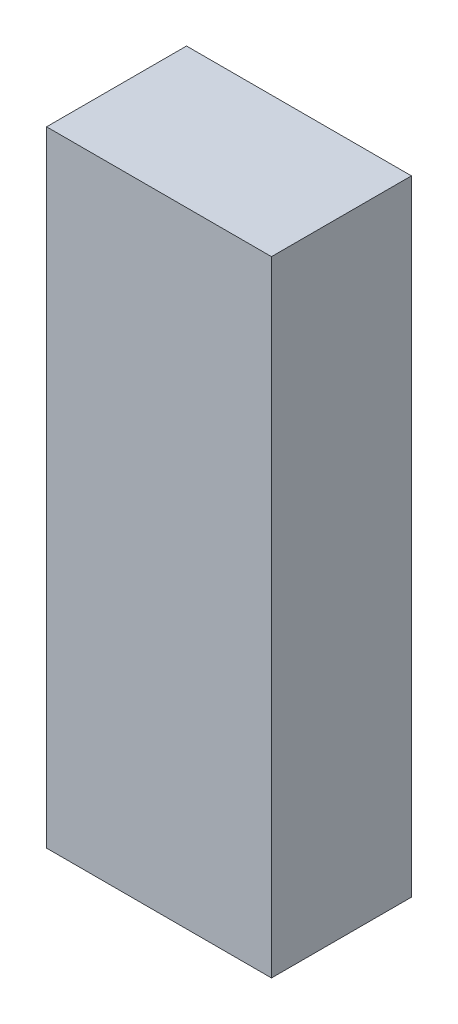
SolidWorks part; units mm, degrees
material "Pila"
ref_plane "Alzado" through (0, 0, 0) normal (0, 0, 1) x (1, 0, 0)
ref_plane "Planta" through (0, 0, 0) normal (0, 1, 0) x (1, 0, 0)
ref_plane "Vista lateral" through (0, 0, 0) normal (1, 0, 0) x (0, 0, -1)
sketch "Croquis1" plane through (0, 0, 0) normal (0, 1, 0) x (1, 0, 0)
  line L1 (22.5, -14) -> (-22.5, -14)
  line L2 (22.5, -14) -> (22.5, 14)
  line L3 (22.5, 14) -> (-22.5, 14)
  line L4 (-22.5, -14) -> (-22.5, 14)
  line L5 (22.5, -14) -> (-22.5, 14) construction
  line L6 (22.5, 14) -> (-22.5, -14) construction
  point P0 (0, 0)
  dimension "D1" = 28
  dimension "D2" = 45
extrude "Saliente-Extruir1" add sketch "Croquis1" along normal blind 125
